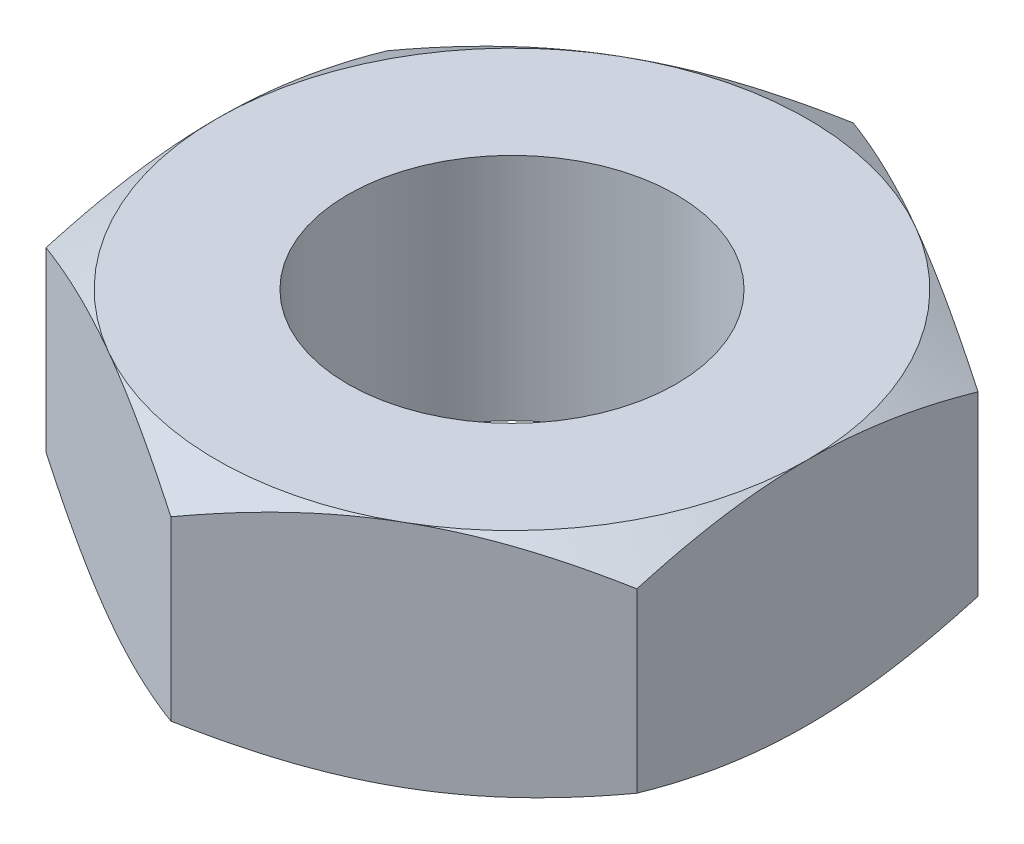
SolidWorks part; units mm, degrees
ref_plane "Front Plane" through (0, 0, 0) normal (0, 0, 1) x (1, 0, 0)
ref_plane "Top Plane" through (0, 0, 0) normal (0, 1, 0) x (1, 0, 0)
ref_plane "Right Plane" through (0, 0, 0) normal (1, 0, 0) x (0, 0, -1)
sketch "Sketch1" plane through (0, 0, 0) normal (0, 1, 0) x (1, 0, 0)
  line L1 (0, 2.5981) -> (-2.25, 1.299)
  line L2 (-2.25, 1.299) -> (-2.25, -1.299)
  line L3 (-2.25, -1.299) -> (0, -2.5981)
  line L4 (0, -2.5981) -> (2.25, -1.299)
  line L5 (2.25, -1.299) -> (2.25, 1.299)
  line L6 (2.25, 1.299) -> (0, 2.5981)
  circle A0 centre (0, 0) radius 2.25 construction
  circle A1 centre (0, 0) radius 1.25
  dimension "D1" = 2.5
  dimension "D2" = 4.5
extrude "Boss-Extrude1" add sketch "Sketch1" along normal blind 1.75
sketch "Sketch2" plane through (0, 1.75, 0) normal (0, 1, 0) x (1, 0, 0)
  circle A0 centre (0, 0) radius 2.25 construction
  circle A1 centre (0, 0) radius 2.25
extrude "Cut-Extrude1" cut sketch "Sketch2" against normal blind 2 draft 60 flip side to cut
ref_plane "Plane1" through (0, 0.875, 0) normal (0, 1, 0) x (1, 0, 0)
mirror "Mirror1" about plane through (0, 0.875, 0) normal (0, 1, 0) of "Cut-Extrude1"
